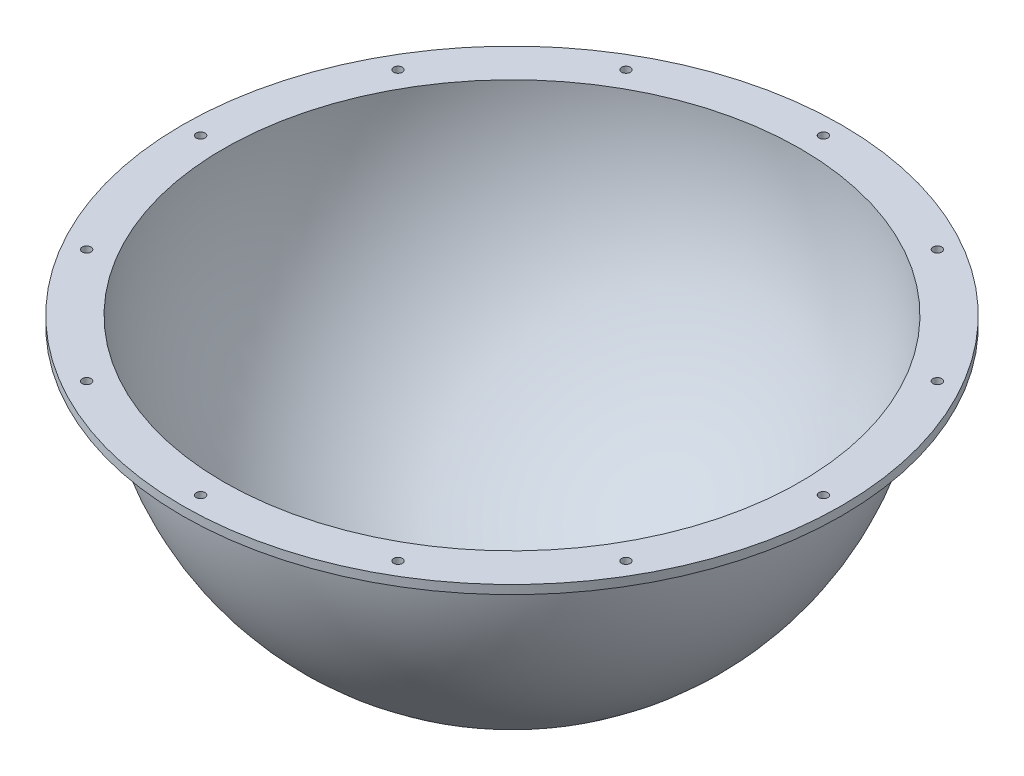
SolidWorks part; units mm, degrees
material "AISI 1020 Steel, Cold Rolled"
ref_plane "Front Plane" through (0, 0, 0) normal (0, 0, 1) x (1, 0, 0)
ref_plane "Top Plane" through (0, 0, 0) normal (0, 1, 0) x (1, 0, 0)
ref_plane "Right Plane" through (0, 0, 0) normal (1, 0, 0) x (0, 0, -1)
sketch "Sketch1" plane through (0, 0, 0) normal (0, 1, 0) x (1, 0, 0)
  line L0 (0, 400) -> (0, 393.75)
  line L1 (0, -393.75) -> (0, -400)
  line L2 (0, 400) -> (0, -400) construction
  arc A0 (0, 400) -> (0, -400) centre (0, 0) ccw
  arc A1 (0, 393.75) -> (0, -393.75) centre (0, 0) ccw
  dimension "D1" = 800
  dimension "D2" = 6.25
revolve "Revolve1" add sketch "Sketch1" angle 180 about L2
ref_axis "Axis1" through (0, 0, 0) along (0, 1, 0)
sketch "Sketch3" plane through (0, 0, 0) normal (1, 0, 0) x (0, 0, -1)
  line L0 (-400, 0) -> (-450, 0)
  line L1 (-450, 0) -> (-450, -12)
  line L2 (-450, -12) -> (-399.82, -12)
  line L3 (-450, 0) -> (450, 0) construction
  arc A0 (-400, 0) -> (400, 0) centre (0, 0) ccw construction
  arc A1 (-400, 0) -> (-399.82, -12) centre (0, 0) ccw
  dimension "D1" = 900
  dimension "D2" = 12
revolve "Revolve2" add sketch "Sketch3" angle 360 about axis through (0, 0, 0) along (0, 1, 0)
sketch "Sketch10" plane through (0, 0, 0) normal (0, 1, 0) x (1, 0, 0)
  circle A0 centre (0, 0) radius 425 construction
  circle A1 centre (0, 425) radius 6
  circle A2 centre (-212.5, 368.0608) radius 6
  circle A3 centre (-368.0608, 212.5) radius 6
  circle A4 centre (-425, 0) radius 6
  circle A5 centre (-368.0608, -212.5) radius 6
  circle A6 centre (-212.5, -368.0608) radius 6
  circle A7 centre (0, -425) radius 6
  circle A8 centre (212.5, -368.0608) radius 6
  circle A9 centre (368.0608, -212.5) radius 6
  circle A10 centre (425, 0) radius 6
  circle A11 centre (368.0608, 212.5) radius 6
  circle A12 centre (212.5, 368.0608) radius 6
  point P30 (0, 0)
  dimension "D2" = 12
  dimension "D1" = 850
  dimension "D3" = 12
extrude "Cut-Extrude1" cut sketch "Sketch10" against normal through all
equation "\"mbtOD\" = 500"
equation "\"mbtT\" = 6"
equation "\"mbtL\" = 3000"
equation "\"mbtFlangeOD\" = 650"
equation "\"mbtFlangeT\" = 12"
equation "\"mbtFlangeBoltCircleDia\" = 650"
equation "\"mbtFlangeHoleDia\" = 12"
equation "\"mbtOringSize\" = 10 "
equation "\"mbtOringDia\" = 620"
equation "\"mbtWidth\" = 2250"
equation "\"skiWidth\" = 1250"
equation "\"mbtCapL\" = 500"
equation "\"vbtRearOD\" = 800"
equation "\"vbtRearT\" = 6.25"
equation "\"vbtRearFlangeOD\" = 900"
equation "\"vbtRearFlangeT\" = 12"
equation "\"vbtRearBoltHoleDia\" = 12"
equation "\"D1@Sketch1\"=\"vbtRearOD\""
equation "\"D2@Sketch1\"=\"vbtRearT\""
equation "\"D1@Sketch3\"=\"vbtRearFlangeOD\""
equation "\"D2@Sketch3\"=\"vbtRearFlangeT\""
equation "\"D1@Sketch10\"=(\"vbtRearOD\"+\"vbtRearFlangeOD\")/2"
equation "\"D2@Sketch10\"=\"vbtRearBoltHoleDia\""
